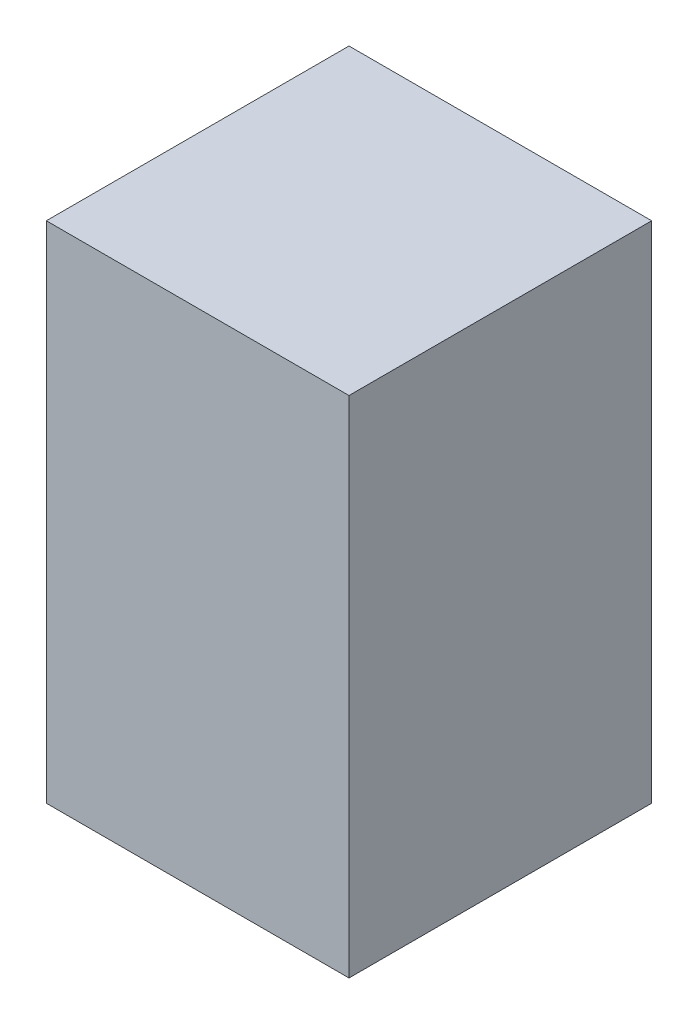
SolidWorks part; units mm, degrees
ref_plane "Front Plane" through (0, 0, 0) normal (0, 0, 1) x (1, 0, 0)
ref_plane "Top Plane" through (0, 0, 0) normal (0, 1, 0) x (1, 0, 0)
ref_plane "Right Plane" through (0, 0, 0) normal (1, 0, 0) x (0, 0, -1)
sketch "Sketch1" plane through (0, 0, 0) normal (0, 0, 1) x (1, 0, 0)
  line L1 (-15, 25) -> (15, 25)
  line L2 (-15, 25) -> (-15, -25)
  line L3 (-15, -25) -> (15, -25)
  line L4 (15, 25) -> (15, -25)
  line L5 (-15, 25) -> (15, -25) construction
  line L6 (-15, -25) -> (15, 25) construction
  point P0 (0, 0)
  dimension "D1" = 30
  dimension "D2" = 50
extrude "Boss-Extrude1" add sketch "Sketch1" along normal blind 30
